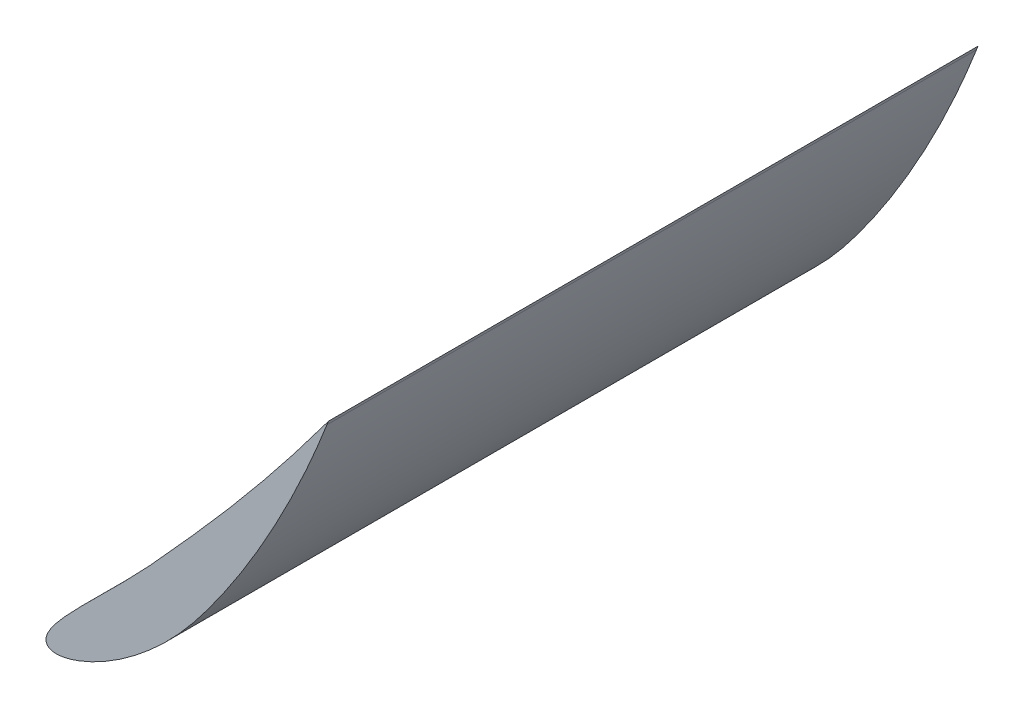
SolidWorks part; units mm, degrees
ref_plane "Front Plane" through (0, 0, 0) normal (0, 0, 1) x (1, 0, 0)
ref_plane "Top Plane" through (0, 0, 0) normal (0, 1, 0) x (1, 0, 0)
ref_plane "Right Plane" through (0, 0, 0) normal (1, 0, 0) x (0, 0, -1)
sketch "Sketch1" plane through (0, 0, 0) normal (0, 0, 1) x (1, 0, 0)
  line L12 (97.9608, 116.7452) -> (0, 0) construction
  line L13 (97.8137, 116.8686) -> (98.1079, 116.6217) construction
  line L15 (0, 0) -> (49.9996, 0) construction
  line L16 (97.8137, 116.8686) -> (98.6313, 117.9703)
  line L17 (98.1079, 116.6217) -> (98.6313, 117.9703)
  spline S1 degree 3 poles (98.1079, 116.6217) (98.078, 116.5447) (97.9586, 116.2369) (97.6893, 115.547) (97.24, 114.4041) (96.609, 112.8187) (95.7949, 110.8051) (94.7958, 108.3814) (93.6103, 105.5688) (92.2372, 102.3918) (90.6758, 98.8777) (88.9259, 95.0561) (86.9894, 90.9584) (84.8681, 86.618) (82.5656, 82.0696) (80.0873, 77.3488) (77.4395, 72.4922) (74.6305, 67.5364) (71.6693, 62.5189) (68.5669, 57.4767) (65.3365, 52.446) (61.9911, 47.4634) (58.5472, 42.5631) (55.0189, 37.7816) (51.4365, 33.1412) (47.735, 28.7388) (43.9472, 24.5981) (40.1019, 20.7397) (36.2318, 17.1804) (32.3721, 13.9326) (28.5592, 11.0057) (24.8318, 8.4049) (21.2285, 6.1329) (17.7884, 4.1892) (14.5496, 2.5708) (11.5478, 1.2736) (8.8169, 0.2907) (6.3858, -0.3841) (4.2781, -0.7594) (2.5079, -0.8411) (1.0759, -0.6301) (-0.0161, -0.0982) (-0.6948, 0.7928) (-0.8263, 1.9585) (-0.496, 3.2915) (0.2362, 4.8342) (1.3655, 6.6037) (2.8807, 8.6045) (4.7662, 10.8349) (7.0008, 13.2915) (9.5597, 15.9697) (12.4137, 18.8651) (15.5313, 21.9715) (18.8777, 25.2834) (22.4167, 28.7935) (26.1102, 32.4941) (29.9196, 36.3755) (33.806, 40.427) (37.7324, 44.6347) (41.6582, 48.9875) (45.6323, 53.3931) (49.6131, 57.8412) (53.5742, 62.3059) (57.4859, 66.7641) (61.322, 71.19) (65.0573, 75.5577) (68.6688, 79.8401) (72.136, 84.0095) (75.4391, 88.0386) (78.5617, 91.8995) (81.4879, 95.5652) (84.2044, 99.0095) (86.6982, 102.2077) (88.959, 105.1361) (90.9768, 107.7733) (92.7432, 110.0996) (94.2504, 112.098) (95.4925, 113.7536) (96.464, 115.054) (97.1608, 115.99) (97.5803, 116.5541) (97.767, 116.8056) (97.8137, 116.8686) knots 0 0 0 0 0.000791 0.00316 0.007087 0.012544 0.019489 0.027873 0.037633 0.048699 0.060994 0.074433 0.088923 0.104368 0.120665 0.13771 0.155392 0.173601 0.192223 0.211146 0.230254 0.249435 0.268577 0.287568 0.306301 0.324671 0.342595 0.359992 0.376786 0.392898 0.408252 0.422771 0.43638 0.449003 0.46057 0.471014 0.48028 0.488325 0.495133 0.500728 0.505217 0.508863 0.51207 0.515471 0.519696 0.525078 0.53175 0.539754 0.54908 0.559692 0.571531 0.584528 0.598598 0.61365 0.629586 0.6463 0.663686 0.681632 0.700027 0.718761 0.737727 0.756809 0.775888 0.794846 0.813569 0.83194 0.849847 0.86718 0.883834 0.899707 0.914701 0.928723 0.941687 0.953513 0.964128 0.973465 0.981467 0.988083 0.993272 0.997002 0.999249 1 1 1 1
  point P10 (97.9608, 116.7452)
  dimension "D1" = 50
  dimension "D2" = 152.4
extrude "Boss-Extrude1" add sketch "Sketch1" along normal blind 228.6
sketch "Sketch2" plane through (0, 0, 228.6) normal (0, 0, 1) x (1, 0, 0)
  line L0 (97.8137, 116.8686) -> (98.1079, 116.6217) construction
  line L1 (97.9608, 116.7452) -> (0, 0) construction
  line L2 (98.1079, 116.6217) -> (98.6313, 117.9703)
  line L3 (98.6313, 117.9703) -> (97.8137, 116.8686)
  line L4 (98.1079, 116.6217) -> (98.6313, 117.9703) construction
  line L5 (98.6313, 117.9703) -> (97.8137, 116.8686) construction
  line L6 (0, 0) -> (-10.9759, 9.2098) construction
  spline S1 degree 3 poles (2576.9286, -1569.6045) (142.5563, 186.6838) (122.2873, 149.7758) (97.1608, 115.99) (96.464, 115.054) (95.4925, 113.7536) (94.2504, 112.098) (92.7432, 110.0996) (90.9768, 107.7733) (88.959, 105.1361) (86.6982, 102.2077) (84.2044, 99.0095) (81.4879, 95.5652) (78.5617, 91.8995) (75.4391, 88.0386) (72.136, 84.0095) (68.6688, 79.8401) (65.0573, 75.5577) (61.322, 71.19) (57.4859, 66.7641) (53.5742, 62.3059) (49.6131, 57.8412) (45.6323, 53.3931) (41.6582, 48.9875) (37.7324, 44.6347) (33.806, 40.427) (29.9196, 36.3755) (26.1102, 32.4941) (22.4167, 28.7935) (18.8777, 25.2834) (15.5313, 21.9715) (12.4137, 18.8651) (9.5597, 15.9697) (7.0008, 13.2915) (4.7662, 10.8349) (2.8807, 8.6045) (1.3655, 6.6037) (0.2362, 4.8342) (-0.496, 3.2915) (-0.8263, 1.9585) (-0.6948, 0.7928) (-0.0161, -0.0982) (1.0759, -0.6301) (2.5079, -0.8411) (4.2781, -0.7594) (6.3858, -0.3841) (8.8169, 0.2907) (11.5478, 1.2736) (14.5496, 2.5708) (17.7884, 4.1892) (21.2285, 6.1329) (24.8318, 8.4049) (28.5592, 11.0057) (32.3721, 13.9326) (36.2318, 17.1804) (40.1019, 20.7397) (43.9472, 24.5981) (47.735, 28.7388) (51.4365, 33.1412) (55.0189, 37.7816) (58.5472, 42.5631) (61.9911, 47.4634) (65.3365, 52.446) (68.5669, 57.4767) (71.6693, 62.5189) (74.6305, 67.5364) (77.4395, 72.4922) (80.0873, 77.3488) (82.5656, 82.0696) (84.8681, 86.618) (86.9894, 90.9584) (88.9259, 95.0561) (90.6758, 98.8777) (92.2372, 102.3918) (93.6103, 105.5688) (94.7958, 108.3814) (95.7949, 110.8051) (96.609, 112.8187) (97.24, 114.4041) (97.6893, 115.547) (110.5527, 148.5001) (116.4708, 183.7127) (2928.8761, -872.2928) knots -0.396222 -0.396222 -0.396222 -0.396222 0.000751 0.002998 0.006728 0.011917 0.018533 0.026535 0.035872 0.046487 0.058313 0.071277 0.085299 0.100293 0.116166 0.13282 0.150153 0.16806 0.186431 0.205154 0.224112 0.243191 0.262273 0.281239 0.299973 0.318368 0.336314 0.3537 0.370414 0.38635 0.401402 0.415472 0.428469 0.440308 0.45092 0.460246 0.46825 0.474922 0.480304 0.484529 0.48793 0.491137 0.494783 0.499272 0.504867 0.511675 0.51972 0.528986 0.53943 0.550997 0.56362 0.577229 0.591748 0.607102 0.623214 0.640008 0.657405 0.675329 0.693699 0.712432 0.731423 0.750565 0.769746 0.788854 0.807777 0.826399 0.844608 0.86229 0.879335 0.895632 0.911077 0.925567 0.939006 0.951301 0.962367 0.972127 0.980511 0.987456 0.992913 0.99684 0.999209 1.331454 1.331454 1.331454 1.331454 only from (97.8137, 116.8686) to (98.1079, 116.6217)
  spline S2 degree 3 poles (97.8137, 116.8686) (97.767, 116.8056) (97.5803, 116.5541) (97.1608, 115.99) (96.464, 115.054) (95.4925, 113.7536) (94.2504, 112.098) (92.7432, 110.0996) (90.9768, 107.7733) (88.959, 105.1361) (86.6982, 102.2077) (84.2044, 99.0095) (81.4879, 95.5652) (78.5617, 91.8995) (75.4391, 88.0386) (72.136, 84.0095) (68.6688, 79.8401) (65.0573, 75.5577) (61.322, 71.19) (57.4859, 66.7641) (53.5742, 62.3059) (49.6131, 57.8412) (45.6323, 53.3931) (41.6582, 48.9875) (37.7324, 44.6347) (33.806, 40.427) (29.9196, 36.3755) (26.1102, 32.4941) (22.4167, 28.7935) (18.8777, 25.2834) (15.5313, 21.9715) (12.4137, 18.8651) (9.5597, 15.9697) (7.0008, 13.2915) (4.7662, 10.8349) (2.8807, 8.6045) (1.3655, 6.6037) (0.2362, 4.8342) (-0.496, 3.2915) (-0.8263, 1.9585) (-0.6948, 0.7928) (-0.0161, -0.0982) (1.0759, -0.6301) (2.5079, -0.8411) (4.2781, -0.7594) (6.3858, -0.3841) (8.8169, 0.2907) (11.5478, 1.2736) (14.5496, 2.5708) (17.7884, 4.1892) (21.2285, 6.1329) (24.8318, 8.4049) (28.5592, 11.0057) (32.3721, 13.9326) (36.2318, 17.1804) (40.1019, 20.7397) (43.9472, 24.5981) (47.735, 28.7388) (51.4365, 33.1412) (55.0189, 37.7816) (58.5472, 42.5631) (61.9911, 47.4634) (65.3365, 52.446) (68.5669, 57.4767) (71.6693, 62.5189) (74.6305, 67.5364) (77.4395, 72.4922) (80.0873, 77.3488) (82.5656, 82.0696) (84.8681, 86.618) (86.9894, 90.9584) (88.9259, 95.0561) (90.6758, 98.8777) (92.2372, 102.3918) (93.6103, 105.5688) (94.7958, 108.3814) (95.7949, 110.8051) (96.609, 112.8187) (97.24, 114.4041) (97.6893, 115.547) (97.9586, 116.2369) (98.078, 116.5447) (98.1079, 116.6217) knots 0 0 0 0 0.000751 0.002998 0.006728 0.011917 0.018533 0.026535 0.035872 0.046487 0.058313 0.071277 0.085299 0.100293 0.116166 0.13282 0.150153 0.16806 0.186431 0.205154 0.224112 0.243191 0.262273 0.281239 0.299973 0.318368 0.336314 0.3537 0.370414 0.38635 0.401402 0.415472 0.428469 0.440308 0.45092 0.460246 0.46825 0.474922 0.480304 0.484529 0.48793 0.491137 0.494783 0.499272 0.504867 0.511675 0.51972 0.528986 0.53943 0.550997 0.56362 0.577229 0.591748 0.607102 0.623214 0.640008 0.657405 0.675329 0.693699 0.712432 0.731423 0.750565 0.769746 0.788854 0.807777 0.826399 0.844608 0.86229 0.879335 0.895632 0.911077 0.925567 0.939006 0.951301 0.962367 0.972127 0.980511 0.987456 0.992913 0.99684 0.999209 1 1 1 1 construction
  dimension "D1" = 0
